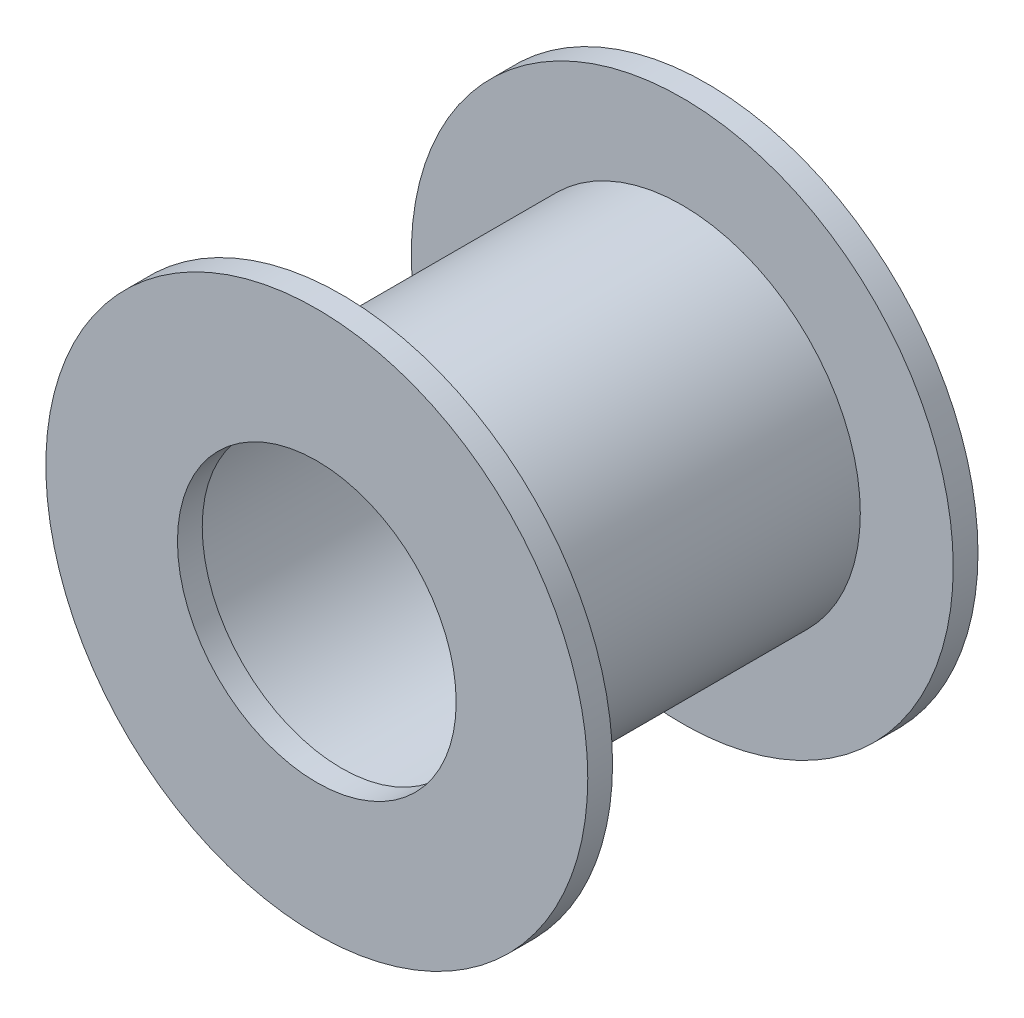
SolidWorks part; units mm, degrees
material "Q235A"
ref_plane "前视" through (0, 0, 0) normal (0, 0, 1) x (1, 0, 0)
ref_plane "上视" through (0, 0, 0) normal (0, 1, 0) x (1, 0, 0)
ref_plane "右视" through (0, 0, 0) normal (1, 0, 0) x (0, 0, -1)
sketch "草图1" plane through (0, 0, 0) normal (0, 0, 1) x (1, 0, 0)
  circle A0 centre (0, 0) radius 175
  dimension "D1" = 350
extrude "凸台-拉伸1" add sketch "草图1" along normal blind 16
sketch "草图2" plane through (0, 0, 16) normal (0, 0, 1) x (1, 0, 0)
  circle A0 centre (0, 0) radius 115
  circle A1 centre (0, 0) radius 105
  dimension "D1" = 10
  dimension "D2" = 230
extrude "凸台-拉伸2" add sketch "草图2" along normal blind 220 separate body
sketch "草图3" plane through (0, 0, 236) normal (0, 0, 1) x (1, 0, 0)
  circle A0 centre (0, 0) radius 175
extrude "凸台-拉伸3" add sketch "草图3" along normal blind 16 separate body
sketch "草图4" plane through (0, 0, 252) normal (0, 0, 1) x (1, 0, 0)
  circle A0 centre (0, 0) radius 90
  dimension "D1" = 180
extrude "切除-拉伸1" cut sketch "草图4" against normal through all
